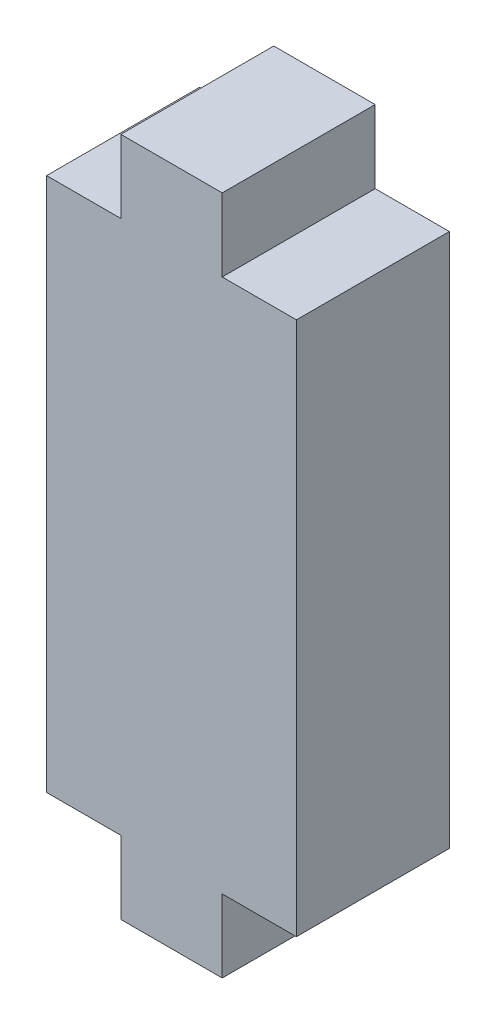
SolidWorks part; units mm, degrees
ref_plane "Front" through (0, 0, 0) normal (0, 0, 1) x (1, 0, 0)
ref_plane "Top" through (0, 0, 0) normal (0, 1, 0) x (1, 0, 0)
ref_plane "Right" through (0, 0, 0) normal (1, 0, 0) x (0, 0, -1)
sketch "Sketch1" plane through (0, 0, 0) normal (0, 0, 1) x (1, 0, 0)
  line L0 (0, 0) -> (4.7625, 0) construction
  line L1 (4.8514, 0) -> (11.4808, 0)
  line L2 (4.7625, 0) -> (4.8514, 0) construction
  line L3 (4.8514, 0) -> (4.8514, 4.7625)
  line L4 (11.4808, 0) -> (11.4808, 4.7625)
  line L5 (11.4808, 4.7625) -> (16.3322, 4.7625)
  line L6 (4.8514, 4.7625) -> (0, 4.7625)
  line L7 (0, 4.7625) -> (0, 39.6875)
  line L8 (0, 39.6875) -> (4.8514, 39.6875)
  line L9 (4.8514, 39.6875) -> (4.8514, 44.45)
  line L10 (4.8514, 44.45) -> (11.4808, 44.45)
  line L11 (11.4808, 44.45) -> (11.4808, 39.6875)
  line L12 (11.4808, 39.6875) -> (16.3322, 39.6875)
  line L13 (16.3322, 39.6875) -> (16.3322, 4.7625)
  dimension "D1" = 4.8514
  dimension "D2" = 4.7625
  dimension "D3" = 6.6294
  dimension "D4" = 34.925
  dimension "D5" = 4.7625
extrude "Boss-Extrude1" add sketch "Sketch1" along normal blind 10
